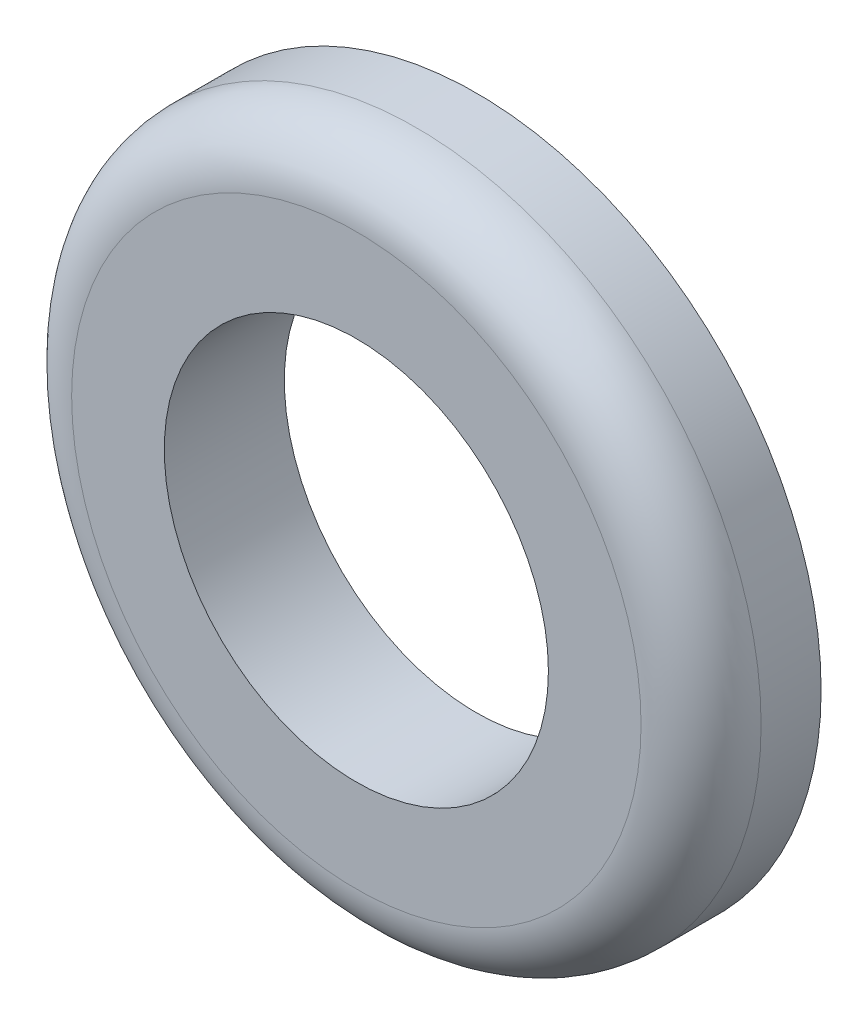
SolidWorks part; units mm, degrees
material "Plastique personnalisé"
ref_plane "Plan de face" through (0, 0, 0) normal (0, 0, 1) x (1, 0, 0)
ref_plane "Plan de dessus" through (0, 0, 0) normal (0, 1, 0) x (1, 0, 0)
ref_plane "Plan de droite" through (0, 0, 0) normal (1, 0, 0) x (0, 0, -1)
sketch "Esquisse1" plane through (0, 0, 0) normal (0, 0, 1) x (1, 0, 0)
  circle A0 centre (0, 0) radius 1.6
  circle A1 centre (0, 0) radius 2.8718
  dimension "D1" = 3.2
extrude "Boss.-Extru.1" add sketch "Esquisse1" along normal blind 1
fillet "Congé1" radius 0.5 1 edges at (2.8718, 0, 1)
